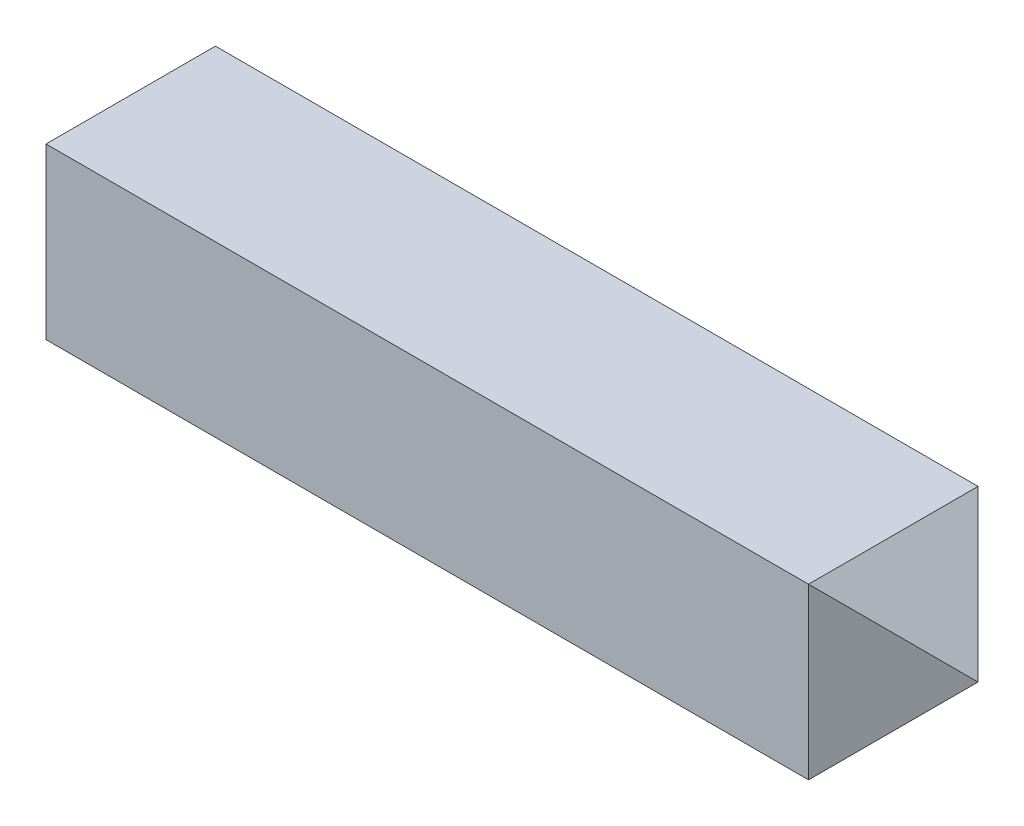
SolidWorks part; units mm, degrees
ref_plane "前视基准面" through (0, 0, 0) normal (0, 0, 1) x (1, 0, 0)
ref_plane "上视基准面" through (0, 0, 0) normal (0, 1, 0) x (1, 0, 0)
ref_plane "右视基准面" through (0, 0, 0) normal (1, 0, 0) x (0, 0, -1)
other "Configuration Table"
sketch "草图1" plane through (0, 0, 0) normal (1, 0, 0) x (0, 0, -1)
  line L1 (-10, -10) -> (10, -10)
  line L2 (-10, -10) -> (-10, 10)
  line L3 (-10, 10) -> (10, 10)
  line L4 (10, -10) -> (10, 10)
  line L5 (-10, -10) -> (10, 10) construction
  line L6 (-10, 10) -> (10, -10) construction
  point P0 (0, 0)
  dimension "D1" = 20
  dimension "D2" = 20
extrude "凸台-拉伸1" add sketch "草图1" along normal blind 100
sketch "草图2" plane through (0, 0, 10) normal (0, 0, 1) x (1, 0, 0)
  line L0 (100, 10) -> (90, 10)
  line L1 (100, 10) -> (0, 10) construction
  line L2 (90, 10) -> (100, 0)
  line L3 (100, 10) -> (100, -10) construction
  line L4 (100, 0) -> (90, -10)
  line L5 (100, -10) -> (0, -10) construction
  line L6 (100, 10) -> (100, 0)
  line L7 (100, 0) -> (100, -10)
  line L8 (100, -10) -> (90, -10)
  line L9 (100, 0) -> (100, -10)
  line L10 (100, 0) -> (100, 10)
  dimension "D1" = 10
  dimension "D2" = 10
extrude "切除-拉伸1" cut sketch "草图2" against normal blind 34 contours L2 L0 L6
sketch "草图3" plane through (0, 0, 10) normal (0, 0, 1) x (1, 0, 0)
  line L0 (100, 0) -> (100, -10)
  line L1 (100, -10) -> (0, -10) construction
  line L2 (100, 0) -> (100, -10) construction
  line L3 (100, -10) -> (90, -10)
  line L4 (90, -10) -> (100, 0)
  dimension "D1" = 10
extrude "切除-拉伸2" cut sketch "草图3" against normal blind 34
sketch "草图4" plane through (0, 10, 0) normal (0, 1, 0) x (1, 0, 0)
  line L0 (100, 0) -> (90, -10)
  line L1 (100, 10) -> (100, -10) construction
  line L2 (90, -10) -> (100, -10)
  line L3 (100, -10) -> (100, 0)
  line L4 (100, 0) -> (100, 10)
  line L5 (100, 10) -> (90, 10)
  line L6 (90, 10) -> (100, 0)
extrude "切除-拉伸3" cut sketch "草图4" against normal blind 34 contours L5 L6 L4 | L2 L3 L0
